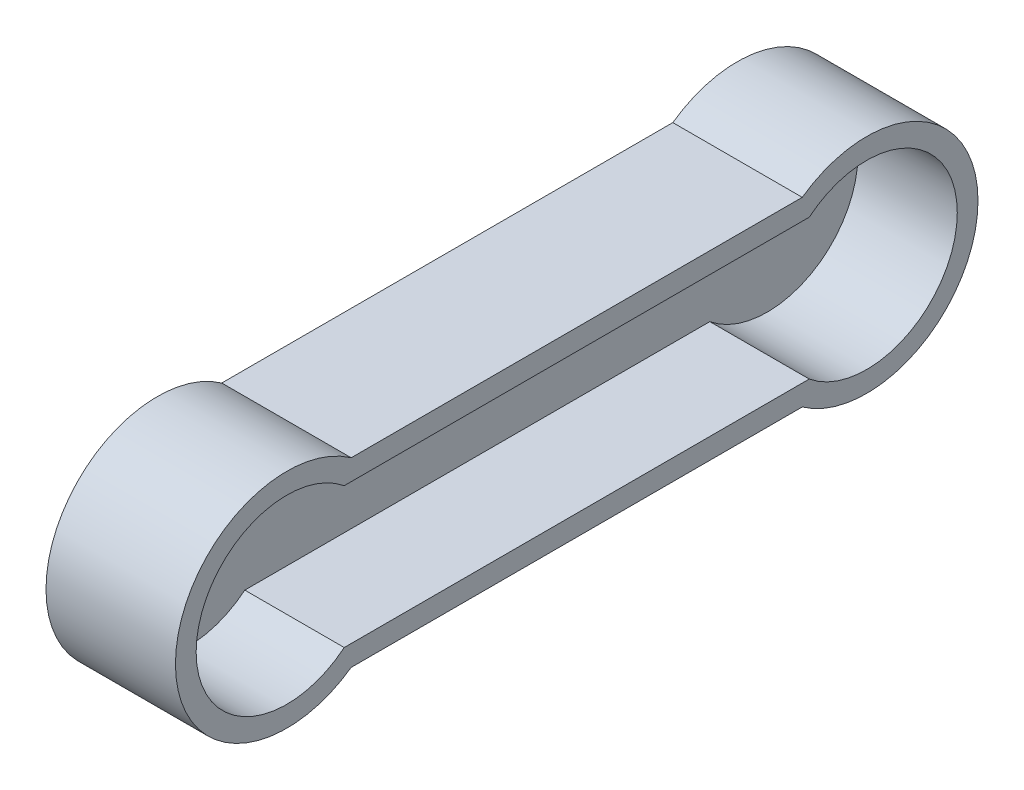
SolidWorks part; units mm, degrees
ref_plane "Alzado" through (0, 0, 0) normal (0, 0, 1) x (1, 0, 0)
ref_plane "Planta" through (0, 0, 0) normal (0, 1, 0) x (1, 0, 0)
ref_plane "Vista lateral" through (0, 0, 0) normal (1, 0, 0) x (0, 0, -1)
sketch "Croquis1" plane through (0, 0, 0) normal (1, 0, 0) x (0, 0, -1)
  line L0 (-52.6944, 0) -> (59.3056, 0) construction
  line L2 (-46.8625, 17.5334) -> (46.8625, 17.5334)
  line L3 (-46.8625, 17.5334) -> (-46.8625, -17.5334)
  line L4 (-46.8625, -17.5334) -> (46.8625, -17.5334)
  line L5 (46.8625, 17.5334) -> (46.8625, -17.5334)
  line L6 (-46.8625, 17.5334) -> (46.8625, -17.5334) construction
  line L7 (-46.8625, -17.5334) -> (46.8625, 17.5334) construction
  circle A0 centre (-52.6944, 0) radius 21.5
  circle A1 centre (59.3056, 0) radius 21.5
  circle A2 centre (-52.6944, 0) radius 5
  circle A3 centre (59.3056, 0) radius 5
  point P5 (0, 0)
extrude "Saliente-Extruir1" add sketch "Croquis1" along normal mid plane 25 contours L2 A0 L4 L3 A2 | L4 A0 L2 L3 | A1 L2 A0 L4 | L5 A1 | L5 A1 A3
sketch "Croquis2" plane through (12.5, 0, 0) normal (1, 0, 0) x (0, 0, -1)
  line L0 (-40.2514, -17.5334) -> (46.8625, -17.5334) construction
  line L1 (-61.9403, 13.5334) -> (61.9403, 13.5334)
  line L2 (-61.9403, 13.5334) -> (-61.9403, -13.5334)
  line L3 (-61.9403, -13.5334) -> (61.9403, -13.5334)
  line L4 (61.9403, 13.5334) -> (61.9403, -13.5334)
  line L5 (-61.9403, 13.5334) -> (61.9403, -13.5334) construction
  line L6 (-61.9403, -13.5334) -> (61.9403, 13.5334) construction
  circle A0 centre (-52.6944, 0) radius 17.5
  circle A1 centre (59.3056, 0) radius 17.5
  arc A2 (-40.2514, 17.5334) -> (-40.2514, -17.5334) centre (-52.6944, 0) ccw construction
  arc A3 (46.8625, -17.5334) -> (46.8625, 17.5334) centre (59.3056, 0) ccw construction
  point P0 (0, 0)
  circle M6 centre (-52.6944, 0) radius 5
  circle M7 centre (59.3056, 0) radius 5
  dimension "D2" = 4
  dimension "D3" = 4
  dimension "D1" = 4
extrude "Cortar-Extruir1" cut sketch "Croquis2" against normal blind 19.2 contours L1 A0 L3 L2 | L3 A0 L1 L2 M6 | A1 L1 A0 L3 | L1 A1 L3 L4 M7 | L3 A1 L1 L4 M7
